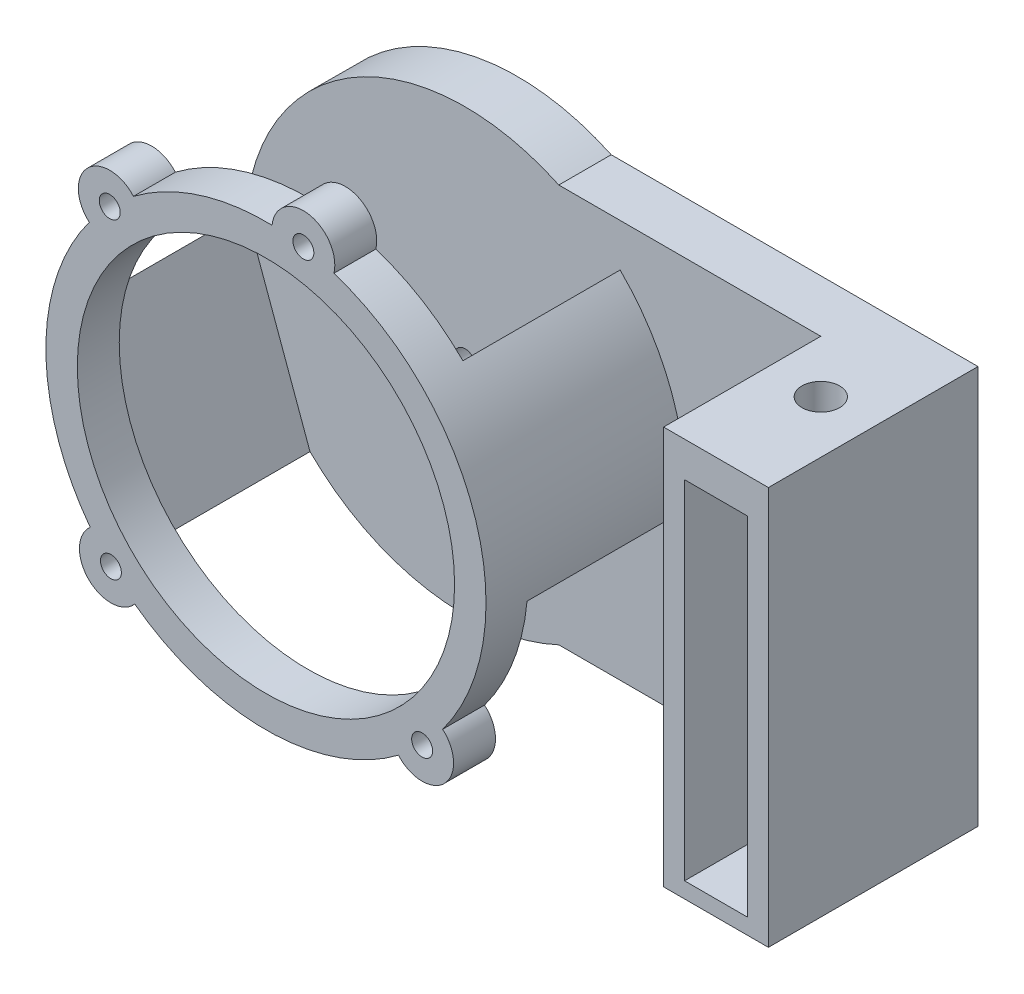
SolidWorks part; units mm, degrees
material "PET"
ref_plane "Piano frontale" through (0, 0, 0) normal (0, 0, 1) x (1, 0, 0)
ref_plane "Piano superiore" through (0, 0, 0) normal (0, 1, 0) x (1, 0, 0)
ref_plane "Piano destro" through (0, 0, 0) normal (1, 0, 0) x (0, 0, -1)
sketch "Schizzo1" plane through (0, 0, 0) normal (0, 0, 1) x (1, 0, 0)
  line L0 (12.3655, 11.6094) -> (47.3655, 11.6094) construction
  line L1 (12.3655, -26.3906) -> (47.3655, -26.3906)
  line L2 (47.3655, -26.3906) -> (47.3655, 11.6094)
  line L3 (47.3655, 11.6094) -> (12.3655, 11.6094)
  arc A2 (12.3655, 11.6094) -> (12.3655, -26.3906) centre (3.4212, -7.3906) ccw
  dimension "D1" = 35
  dimension "D4" = 35
  dimension "D3" = 42
  dimension "D2" = 38
extrude "Estrusione-Estrusione1" add sketch "Schizzo1" along normal mid plane 5
sketch "Schizzo2" plane through (0, 0, 2.5) normal (0, 0, 1) x (1, 0, 0)
  line L1 (37.3655, 11.6094) -> (47.3655, 11.6094)
  line L2 (37.3655, 11.6094) -> (37.3655, -26.3906)
  line L3 (37.3655, -26.3906) -> (47.3655, -26.3906)
  line L4 (47.3655, 11.6094) -> (47.3655, -26.3906)
  line L5 (37.3655, 11.6094) -> (47.3655, -26.3906) construction
  line L6 (37.3655, -26.3906) -> (47.3655, 11.6094) construction
  point P0 (42.3655, -7.3906)
  dimension "D1" = 10
extrude "Estrusione-Estrusione2" add sketch "Schizzo2" along normal blind 15
sketch "Schizzo3" plane through (0, 0, 17.5) normal (0, 0, 1) x (1, 0, 0)
  line L1 (39.3655, 8.2594) -> (45.3655, 8.2594)
  line L2 (39.3655, 8.2594) -> (39.3655, -24.8906)
  line L3 (39.3655, -24.8906) -> (45.3655, -24.8906)
  line L4 (45.3655, 8.2594) -> (45.3655, -24.8906)
  line L5 (39.3655, 8.2594) -> (45.3655, -24.8906) construction
  line L6 (39.3655, -24.8906) -> (45.3655, 8.2594) construction
  line L7 (47.3655, -26.3906) -> (47.3655, 11.6094) construction
  line L8 (37.3655, -26.3906) -> (47.3655, -26.3906) construction
  point P0 (42.3655, -8.3156)
  dimension "D1" = 6
  dimension "D2" = 2
  dimension "D3" = 33.15
  dimension "D4" = 1.5
extrude "Taglio-Estrusione1" cut sketch "Schizzo3" against normal blind 20
sketch "Schizzo5" plane through (0, 0, 2.5) normal (0, 0, 1) x (1, 0, 0)
  line L0 (37.3655, -7.3906) -> (-17.5788, -7.3906) construction
  line L1 (37.3655, 11.6094) -> (37.3655, -26.3906) construction
  line L3 (3.4212, -28.3906) -> (3.4212, 13.6094) construction
  arc A0 (12.3655, 11.6094) -> (12.3655, -26.3906) centre (3.4212, -7.3906) ccw construction
  circle A1 centre (3.4212, -7.3906) radius 21
extrude "Estrusione-Sottile1" add sketch "Schizzo5" along normal blind 19 thin thin type one direction reverse wall 3
sketch "Schizzo7" plane through (0, 0, 2.5) normal (0, 0, 1) x (1, 0, 0)
  line L0 (39.3655, -24.8906) -> (45.3655, -22.7068) construction
  line L1 (45.3655, -24.8906) -> (45.3655, 8.2594) construction
  line L2 (39.3655, -24.8906) -> (41.0192, -29.4343) construction
  line L3 (39.3655, -24.8906) -> (45.3655, -24.8906) construction
  line L4 (45.3655, -24.8906) -> (39.3655, -24.8906) construction
  dimension "D1" = 20
ref_plane "Piano1" through (-4.4069, 12.1079, 0) normal (-0.342, 0.9397, 0) x (0.9397, 0.342, 0)
sketch "Schizzo8" plane through (-4.4069, 12.1079, 0) normal (-0.342, 0.9397, 0) x (0.9397, 0.342, 0)
  line L6 (0.6872, -21.5) -> (0.6872, 2.5) construction
  line L7 (-20.3128, -21.5) -> (21.6872, -21.5) construction
  line L8 (15.5904, 2.5) -> (-20.3128, 2.5) construction
  line L9 (-18.3128, -17.5) -> (19.6872, -17.5)
  line L10 (19.6872, -17.5) -> (19.6872, -2.5)
  line L11 (2.5936, -2.5) -> (21.6872, -2.5) construction
  line L12 (19.6872, -2.5) -> (-18.3128, -2.5)
  line L13 (-18.3128, -2.5) -> (-18.3128, -17.5)
  dimension "D1" = 19
  dimension "D2" = 38
  dimension "D3" = 4
extrude "Taglio-Estrusione2" cut sketch "Schizzo8" against normal through all
sketch "Schizzo10" plane through (0, 0, 21.5) normal (0, 0, 1) x (1, 0, 0)
  line L0 (-11.3738, -22.2939) -> (18.2163, 7.5126) construction
  line L1 (3.4212, -7.3906) -> (6.9925, 13.3035) construction
  line L2 (18.3245, -22.1857) -> (-11.482, 7.4044) construction
  circle A0 centre (3.4212, -7.3906) radius 21 construction
  circle A2 centre (-11.482, 7.4044) radius 3
  circle A4 centre (18.3245, -22.1857) radius 3
  circle A5 centre (-11.3738, -22.2939) radius 3
  arc A6 (24.3345, -9.2971) -> (18.2163, 7.5126) centre (3.4212, -7.3906) ccw construction
  circle A7 centre (6.9925, 13.3035) radius 3
  dimension "D2" = 6
  dimension "D3" = 6
  dimension "D4" = 21
  dimension "D5" = 6
  dimension "D1" = 42
  dimension "D6" = 35
  dimension "D7" = 21
extrude "Estrusione-Estrusione3" add sketch "Schizzo10" against normal blind 4
hole_wizard "Foro per Vite M1.6-1" positions "Schizzo3D1" profile "Schizzo11" hole size "M1.6" standard "ISO"
sketch3d "Schizzo3D1"
  point P0 (6.9925, 13.3035, 21.5)
  point P3 (-11.482, 7.4044, 21.5)
  point P6 (-11.3738, -22.2939, 21.5)
  point P9 (18.3245, -22.1857, 21.5)
sketch "Schizzo11" plane through (6.9925, 13.3035, 21.5) normal (1, 0, 0) x (0, -1, 0)
  line L0 (0, 0) -> (0, 3.6009)
  line L1 (0, 3.6009) -> (1, 3)
  line L2 (1, 3) -> (1, 0)
  line L5 (1, 0) -> (0, 0)
  line L10 (0, 3.6009) -> (-1, 3) construction
  line L11 (0, -6.35) -> (0, 107.95) construction
  dimension "Hole Dia." = 2
  dimension "Hole Depth" = 3
  dimension "Drill Angle" = 118
sketch "Schizzo12" plane through (0, 0, 2.5) normal (0, 0, 1) x (1, 0, 0)
  line L0 (3.4212, -28.3906) -> (3.4212, -7.3906) construction
  arc A0 (-9.0992, -24.25) -> (16.0642, -24.1583) centre (3.4212, -7.3906) ccw construction
  arc A1 (-9.0992, -24.25) -> (16.0642, -24.1583) centre (3.4212, -7.3906) ccw construction
  circle A2 centre (3.4212, -7.3906) radius 1
  dimension "D1" = 2
extrude "Taglio-Estrusione3" cut sketch "Schizzo12" against normal blind 3
sketch "Schizzo13" plane through (0, 11.6094, 0) normal (0, 1, 0) x (1, 0, 0)
  line L0 (37.3655, -17.5) -> (47.3655, 2.5) construction
  line L1 (47.3655, 2.5) -> (47.3655, -17.5) construction
  line L2 (47.3655, -17.5) -> (37.3655, 2.5) construction
  line L3 (47.3655, 2.5) -> (12.3655, 2.5) construction
  dimension "D1" = 10
hole_wizard "Foro per Vite M3-1" positions "Schizzo3D5" profile "Schizzo19" hole size "M3" standard "ISO"
sketch3d "Schizzo3D5"
  line L0 (37.3655, 11.6094, 17.5) -> (47.3655, 11.6094, -2.5) construction
  line L1 (47.3655, 11.6094, 17.5) -> (37.3655, 11.6094, -2.5) construction
  point P0 (42.3655, 11.6094, 7.5)
  point P4 (42.3655, 11.6094, 7.5)
  point P6 (42.3655, 11.6094, 7.5)
  point P8 (42.3655, 11.6094, 7.5)
  point P10 (42.3655, 11.6094, 7.5)
  point P15 (42.3655, 11.6094, 7.5)
sketch "Schizzo19" plane through (42.3655, 11.6094, 7.5) normal (1, 0, 0) x (0, 0, 1)
  line L0 (0, 0) -> (0, 5.0815)
  line L1 (0, 5.0815) -> (1.8, 4)
  line L2 (1.8, 4) -> (1.8, 0)
  line L5 (1.8, 0) -> (0, 0)
  line L10 (0, 5.0815) -> (-1.8, 4) construction
  line L11 (0, -6.35) -> (0, 107.95) construction
  dimension "Hole Dia." = 3.6
  dimension "Hole Depth" = 4
  dimension "Drill Angle" = 118
